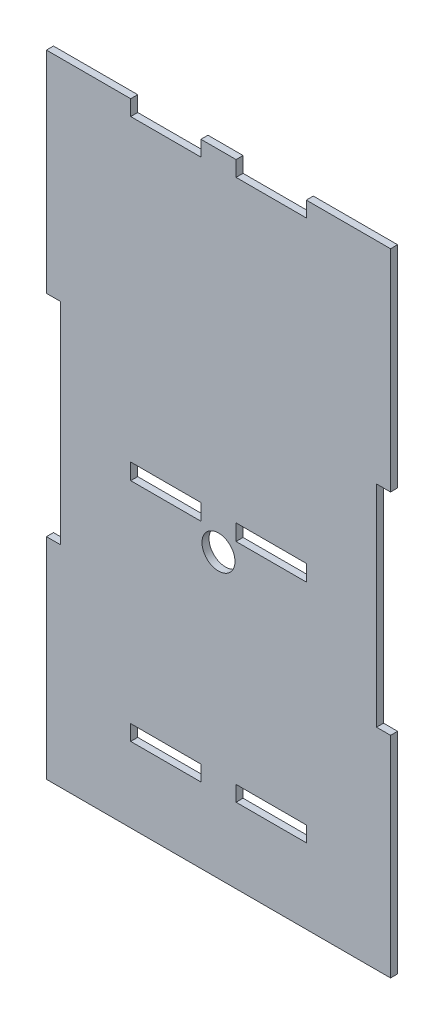
SolidWorks part; units mm, degrees
ref_plane "前视基准面" through (0, 0, 0) normal (0, 0, 1) x (1, 0, 0)
ref_plane "上视基准面" through (0, 0, 0) normal (0, 1, 0) x (1, 0, 0)
ref_plane "右视基准面" through (0, 0, 0) normal (1, 0, 0) x (0, 0, -1)
sketch "Model" plane through (0, 0, 0) normal (0, 0, 1) x (1, 0, 0)
  line L0 (3.0022, 2.6564) -> (33.2522, 2.6564)
  line L1 (33.2522, 2.6564) -> (52.0022, 2.6564)
  line L2 (3.0022, 2.6564) -> (3.0022, 32.5826)
  line L3 (3.0022, 92.5826) -> (15.0022, 92.5826)
  line L4 (52.0022, 2.6564) -> (52.0022, 32.5826)
  line L5 (15.0022, 47.7826) -> (25.0022, 47.7826)
  line L6 (15.0022, 45.4826) -> (25.0022, 45.4826)
  line L7 (15.0022, 15.53) -> (25.0022, 15.53)
  line L8 (15.0022, 13.3299) -> (25.0022, 13.3299)
  line L9 (25.0022, 13.3299) -> (25.0022, 15.53)
  line L10 (30.0022, 13.3299) -> (30.0022, 15.53)
  line L11 (25.0022, 45.4826) -> (25.0022, 47.7826)
  line L12 (30.0022, 45.4826) -> (30.0022, 47.7826)
  line L13 (30.0022, 90.3826) -> (30.0022, 92.5826)
  line L14 (40.0022, 13.3299) -> (40.0022, 15.53)
  line L17 (40.0022, 45.4826) -> (40.0022, 47.7826)
  line L18 (40.0022, 90.3826) -> (40.0022, 92.5826)
  line L19 (15.0022, 13.3299) -> (15.0022, 15.53)
  line L20 (30.0022, 13.3299) -> (40.0022, 13.3299)
  line L21 (30.0022, 15.53) -> (40.0022, 15.53)
  line L22 (15.0022, 90.3826) -> (15.0022, 92.5826)
  line L26 (25.0022, 90.3826) -> (25.0022, 92.5826)
  line L27 (15.0022, 45.4826) -> (15.0022, 47.7826)
  line L28 (30.0022, 47.7826) -> (40.0022, 47.7826)
  line L29 (30.0022, 45.4826) -> (40.0022, 45.4826)
  line L30 (15.0022, 90.3826) -> (25.0022, 90.3826)
  line L31 (40.0022, 90.3826) -> (30.0022, 90.3826)
  line L32 (5.0022, 32.5826) -> (5.0022, 62.5826)
  line L33 (5.0022, 32.5826) -> (3.0022, 32.5826)
  line L34 (5.0022, 62.5826) -> (3.0022, 62.5826)
  line L35 (50.0022, 32.5826) -> (50.0022, 62.5826)
  line L36 (50.0022, 32.5826) -> (52.0022, 32.5826)
  line L37 (50.0022, 62.5826) -> (52.0022, 62.5826)
  line L38 (52.0022, 62.5826) -> (52.0022, 92.5826)
  line L39 (3.0022, 62.5826) -> (3.0022, 92.5826)
  line L40 (40.0022, 92.5826) -> (52.0022, 92.5826)
  line L41 (25.0022, 92.5826) -> (30.0022, 92.5826)
  circle A0 centre (27.5022, 42.9332) radius 2.35
extrude "凸台-拉伸1" add sketch "Model" along normal blind 1
